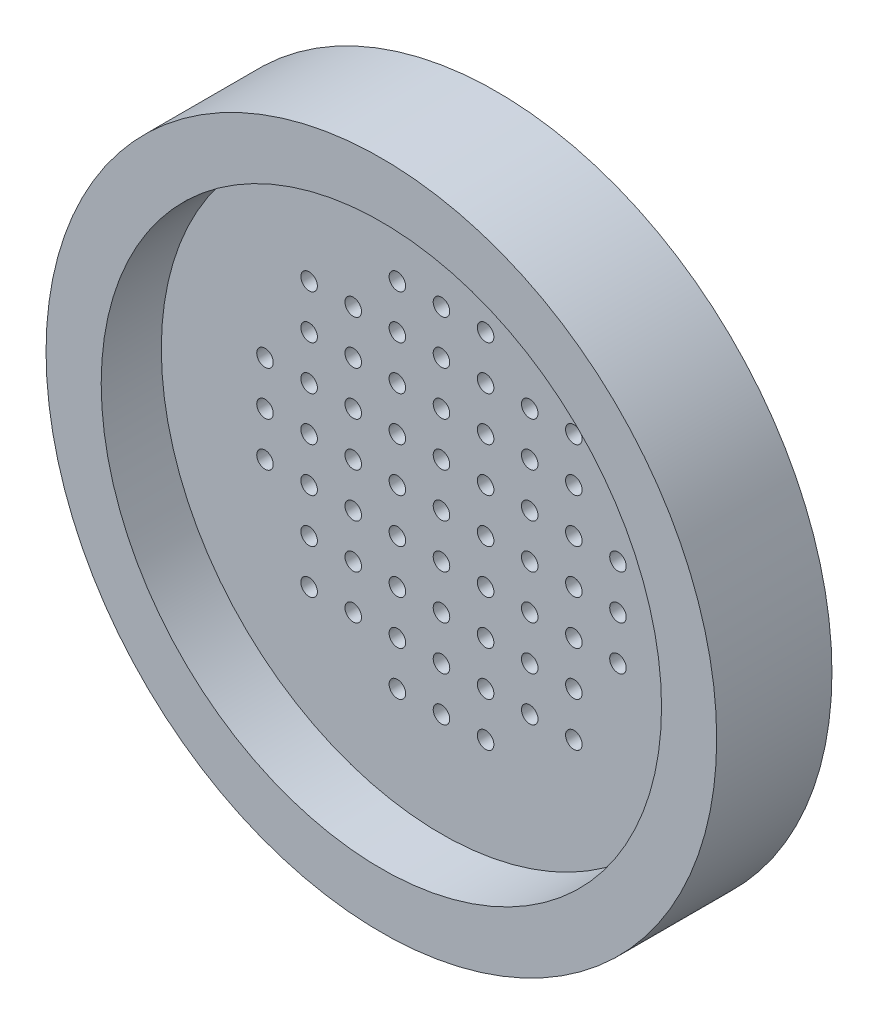
SolidWorks part; units mm, degrees
ref_plane "Plan de face" through (0, 0, 0) normal (0, 0, 1) x (1, 0, 0)
ref_plane "Plan de dessus" through (0, 0, 0) normal (0, 1, 0) x (1, 0, 0)
ref_plane "Plan de droite" through (0, 0, 0) normal (1, 0, 0) x (0, 0, -1)
sketch "Sketch1" plane through (0, 0, 0) normal (0, 0, 1) x (1, 0, 0)
  circle A0 centre (0, 0) radius 30.4
extrude "Boss-Extrude1" add sketch "Sketch1" along normal blind 5
sketch "Sketch2" plane through (0, 0, 5) normal (0, 0, 1) x (1, 0, 0)
  circle A0 centre (0, 0) radius 0.75
extrude "Cut-Extrude1" cut sketch "Sketch2" against normal through all
pattern_linear "LPattern1" count 5 spacing 4 along (0, 1, 0) count 5 spacing 4 along (1, 0, 0) skipping (2, 4), (3, 4), (4, 2), (4, 3), (4, 4) of "Cut-Extrude1"
mirror "Mirror1" about plane through (0, 0, 0) normal (1, 0, 0) of "LPattern1" second plane through (0, 0, 0) second plane normal (0, 1, 0)
sketch "Sketch8" plane through (0, 0, 0) normal (0, 0, -1) x (-1, 0, 0)
  line L0 (-30.4, 0) -> (-26.4, 0)
  line L1 (0, 30.4) -> (0, 27.9)
  circle A0 centre (0, 0) radius 30.4 construction
  circle A1 centre (0, 0) radius 30.4 construction
sketch "Sketch16" plane through (0, 0, 5) normal (0, 0, 1) x (1, 0, 0)
  circle A0 centre (0, 0) radius 25.4
  circle A1 centre (0, 0) radius 30.4
extrude "Boss-Extrude2" add sketch "Sketch16" along normal blind 5.45
